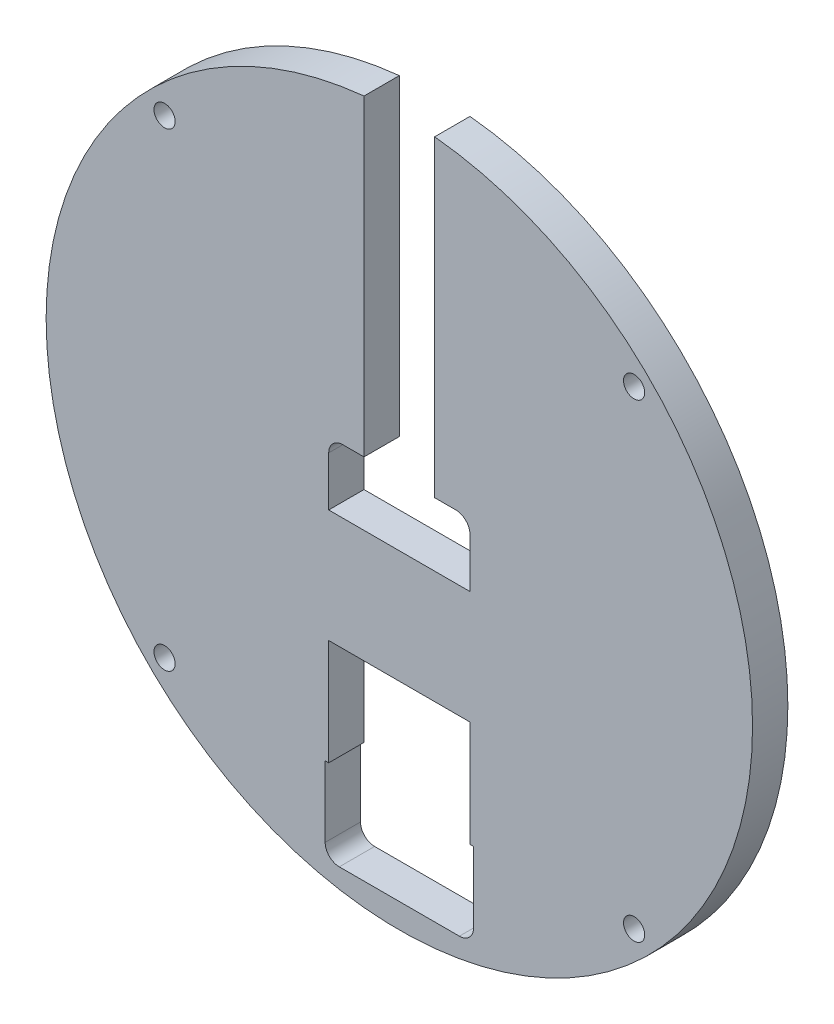
SolidWorks part; units mm, degrees
material "ABS"
ref_plane "前视基准面" through (0, 0, 0) normal (0, 0, 1) x (1, 0, 0)
ref_plane "上视基准面" through (0, 0, 0) normal (0, 1, 0) x (1, 0, 0)
ref_plane "右视基准面" through (0, 0, 0) normal (1, 0, 0) x (0, 0, -1)
sketch "草图1" plane through (0, 0, 0) normal (0, 0, 1) x (1, 0, 0)
  line L0 (0, 0) -> (18.4108, 0) construction
  line L1 (0, 0) -> (17.3647, 17.3647) construction
  line L2 (-5, 49.7494) -> (-5, 5.5)
  line L3 (0, 50) -> (0, 34.8484) construction
  line L4 (5, 49.7494) -> (5, 5.5)
  line L5 (-5, 5.5) -> (5, 5.5) construction
  line L6 (5, 5.5) -> (8, 5.5)
  line L8 (-10, -34.5) -> (-10, -19.5)
  line L9 (-8, 5.5) -> (-5, 5.5)
  line L10 (10, -34.5) -> (10, -19.5)
  line L11 (-8.5, -46.5) -> (8.5, -46.5)
  line L12 (-10.5, -44.5) -> (-10.5, -34.5)
  line L13 (-10.5, -34.5) -> (-10, -34.5)
  line L14 (10.5, -44.5) -> (10.5, -34.5)
  line L15 (-10.5, -46.5) -> (10.5, -34.5) construction
  line L16 (-10.5, -34.5) -> (10.5, -46.5) construction
  line L17 (10, -34.5) -> (10.5, -34.5)
  line L18 (-10, -3.5) -> (10, -3.5)
  line L19 (-10, -19.5) -> (10, -19.5)
  line L20 (-10, -3.5) -> (-10, 3.5)
  line L21 (10, -3.5) -> (10, 3.5)
  circle A0 centre (0, 0) radius 50
  circle A1 centre (33.234, 33.234) radius 1.5
  circle A2 centre (33.234, -33.234) radius 1.5
  circle A3 centre (-33.234, -33.234) radius 1.5
  circle A4 centre (-33.234, 33.234) radius 1.5
  arc A5 (8, 5.5) -> (10, 3.5) centre (8, 3.5) cw
  arc A6 (-10, 3.5) -> (-8, 5.5) centre (-8, 3.5) cw
  arc A7 (8.5, -46.5) -> (10.5, -44.5) centre (8.5, -44.5) ccw
  arc A8 (-8.5, -46.5) -> (-10.5, -44.5) centre (-8.5, -44.5) cw
  point P18 (0, 0)
  point P27 (0, -40.5)
  dimension "D1" = 100
  dimension "D3" = 3
  dimension "D12" = 2
  dimension "D2" = 45
  dimension "D4" = 47
  dimension "D6" = 5
  dimension "D7" = 5.5
  dimension "D8" = 20
  dimension "D9" = 10
  dimension "D10" = 12
  dimension "D11" = 21
  dimension "D13" = 40
  dimension "D14" = 25
  dimension "D15" = 9
  dimension "D5" = 4
extrude "凸台-拉伸1" add sketch "草图1" along normal blind 5 contours L20 A6 L9 L2 A0 L4 L6 A5 L21 L18 A4 A3 A2 A1 L11 A8 L12 L13 L8 L19 L10 L17 L14 A7
